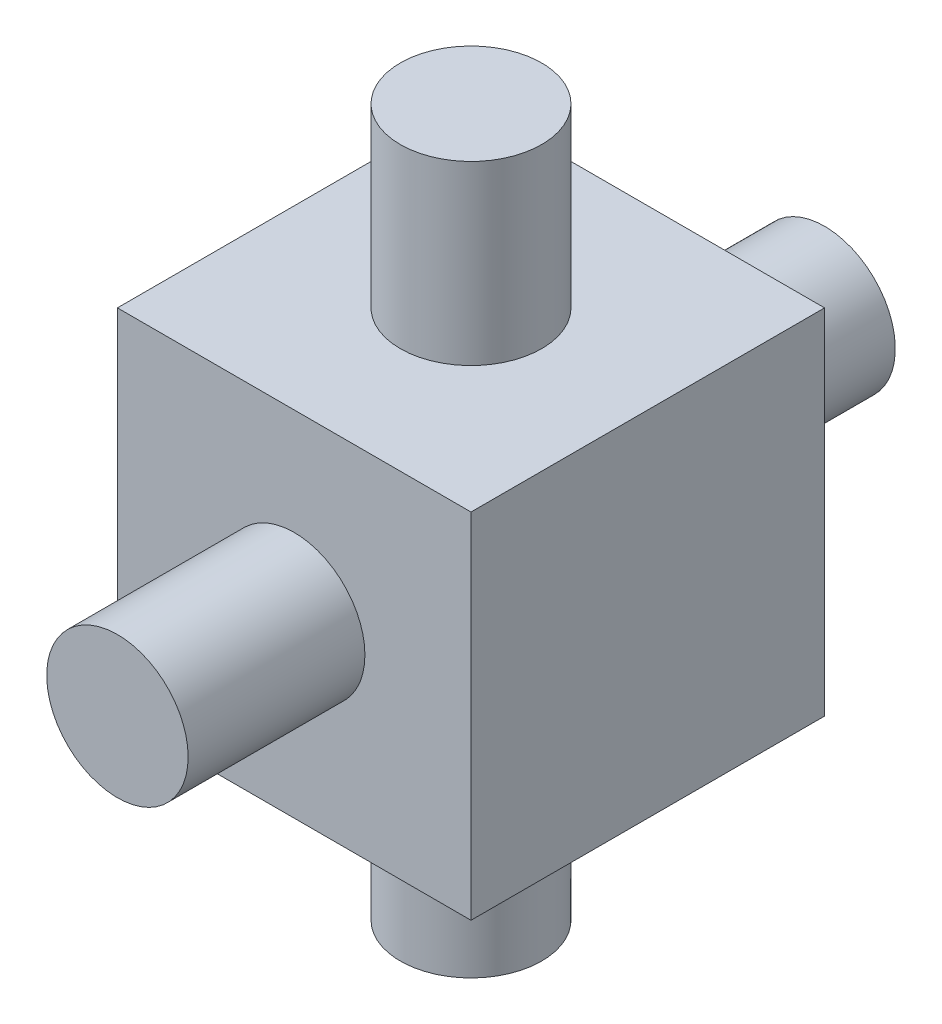
SolidWorks part; units mm, degrees
ref_plane "Front Plane" through (0, 0, 0) normal (0, 0, 1) x (1, 0, 0)
ref_plane "Top Plane" through (0, 0, 0) normal (0, 1, 0) x (1, 0, 0)
ref_plane "Right Plane" through (0, 0, 0) normal (1, 0, 0) x (0, 0, -1)
sketch "Sketch2" plane through (0, 0, 0) normal (0, 1, 0) x (1, 0, 0)
  line L1 (-10, 10) -> (10, 10)
  line L2 (-10, 10) -> (-10, -10)
  line L3 (-10, -10) -> (10, -10)
  line L4 (10, 10) -> (10, -10)
  line L5 (-10, 10) -> (10, -10) construction
  line L6 (-10, -10) -> (10, 10) construction
  point P0 (0, 0)
  dimension "D1" = 20
  dimension "D2" = 20
extrude "Boss-Extrude1" add sketch "Sketch2" along normal mid plane 20
sketch "Sketch3" plane through (0, 10, 0) normal (0, 1, 0) x (1, 0, 0)
  circle A0 centre (0, 0) radius 4
sketch "Sketch4" plane through (0, -10, 0) normal (0, -1, 0) x (1, 0, 0)
  circle A0 centre (0, 0) radius 4
sketch "Sketch5" plane through (0, 0, -10) normal (0, 0, -1) x (-1, 0, 0)
  circle A0 centre (0, 0) radius 4
sketch "Sketch6" plane through (0, 0, 10) normal (0, 0, 1) x (1, 0, 0)
  circle A0 centre (0, 0) radius 4
extrude "Boss-Extrude2" add sketch "Sketch5" along normal blind 10 contours A0
extrude "Boss-Extrude3" add sketch "Sketch3" along normal blind 10 contours A0
extrude "Boss-Extrude4" add sketch "Sketch6" along normal blind 10 contours A0
extrude "Boss-Extrude5" add sketch "Sketch4" along normal blind 10 contours A0
